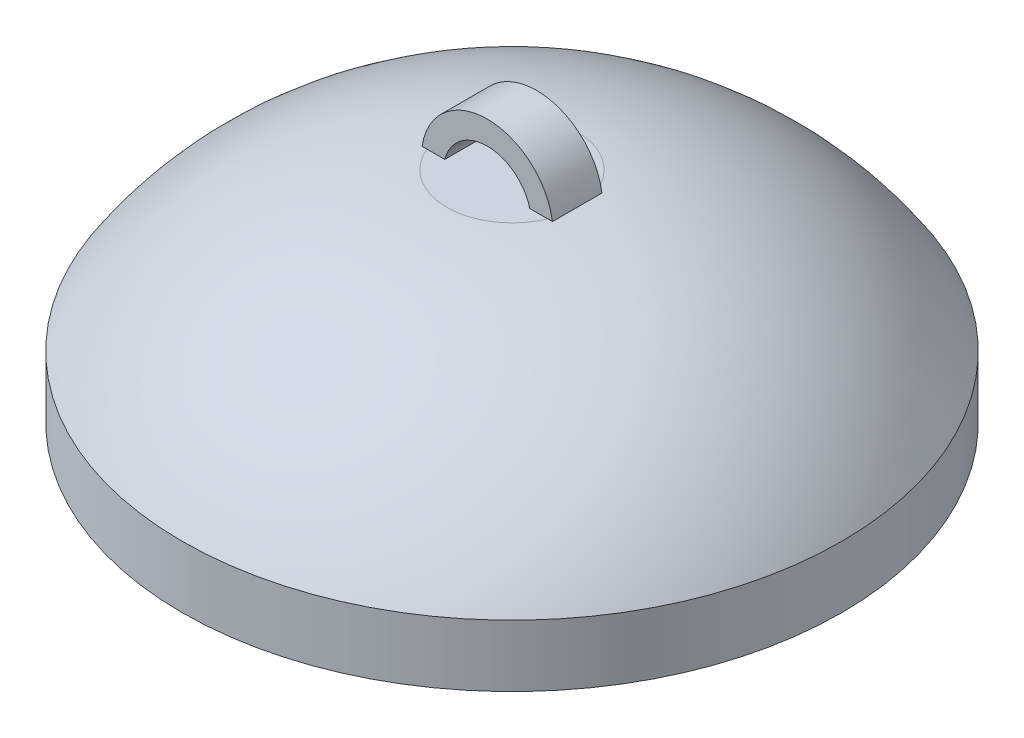
SolidWorks part; units mm, degrees
ref_plane "Plano frontal" through (0, 0, 0) normal (0, 0, 1) x (1, 0, 0)
ref_plane "Plano superior" through (0, 0, 0) normal (0, 1, 0) x (1, 0, 0)
ref_plane "Plano direito" through (0, 0, 0) normal (1, 0, 0) x (0, 0, -1)
sketch "Esboço1" plane through (0, 0, 0) normal (0, 0, 1) x (1, 0, 0)
  line L0 (-80, 0) -> (-72.5, 0)
  line L2 (-80, 0) -> (-80, 15)
  line L4 (-60, 15) -> (-60, 0)
  line L5 (-60, 0) -> (-67.5, 0)
  line L6 (-72.5, 0) -> (-72.5, 5)
  line L7 (-72.5, 5) -> (-67.5, 5)
  line L8 (-67.5, 5) -> (-67.5, 0)
  line L9 (0, 0) -> (0, 40) construction
  line L12 (0, 53.1048) -> (-15.8165, 53.1048)
  line L13 (-13.7333, 40) -> (0, 40)
  line L14 (0, 40) -> (0, 53.1048)
  arc A0 (-60, 15) -> (-13.7333, 40) centre (-3.1751, -34.8519) cw
  arc A1 (-80, 15) -> (-15.8165, 53.1048) centre (-9.7149, -30.2802) cw
  point P4 (0, 0)
  dimension "D1" = 7.5
  dimension "D2" = 20
  dimension "D3" = 15
  dimension "D4" = 7.5
  dimension "D5" = 5
  dimension "D6" = 40
revolve "Revolução1" add sketch "Esboço1" angle 360 about L9
sketch "Esboço2" plane through (0, 0, 0) normal (0, 0, 1) x (1, 0, 0)
  line L0 (15.8165, 53.1048) -> (10.3165, 53.1048)
  line L1 (15.8165, 53.1048) -> (-15.8165, 53.1048) construction
  line L2 (0, 53.1048) -> (0, 64.0992) construction
  line L3 (-15.8165, 53.1048) -> (-10.3165, 53.1048)
  arc A0 (-15.8165, 53.1048) -> (15.8165, 53.1048) centre (0, 50.7659) cw
  arc A1 (-10.3165, 53.1048) -> (10.3165, 53.1048) centre (0, 50.4004) cw
  dimension "D1" = 5.5
extrude "Ressalto-extrusão1" add sketch "Esboço2" along normal mid plane 12
